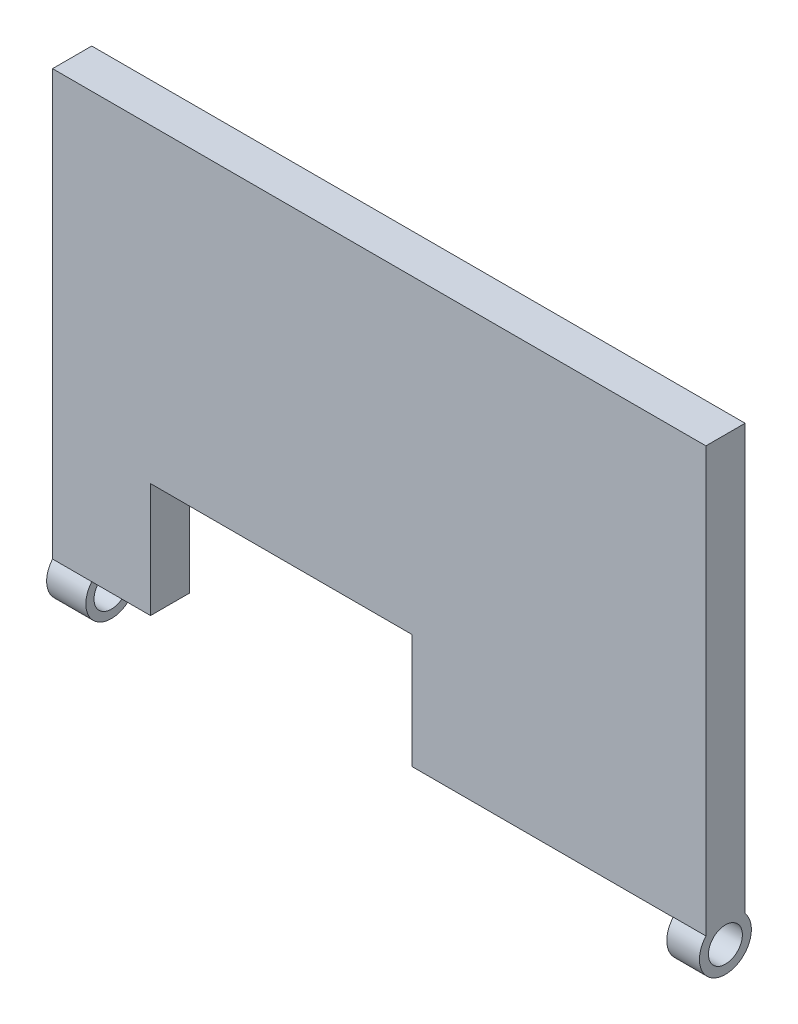
SolidWorks part; units mm, degrees
ref_plane "前视基准面" through (0, 0, 0) normal (0, 0, 1) x (1, 0, 0)
ref_plane "上视基准面" through (0, 0, 0) normal (0, 1, 0) x (1, 0, 0)
ref_plane "右视基准面" through (0, 0, 0) normal (1, 0, 0) x (0, 0, -1)
other "Configuration Table"
sketch "草图1" plane through (0, 0, 0) normal (0, 0, 1) x (1, 0, 0)
  line L0 (0, 0) -> (50, 0)
  line L1 (50, 0) -> (50, 65)
  line L2 (50, 65) -> (-50, 65)
  line L3 (-50, 65) -> (-50, 0)
  line L4 (-50, 0) -> (0, 0)
  dimension "D1" = 50
  dimension "D2" = 65
extrude "凸台-拉伸1" add sketch "草图1" along normal blind 6
sketch "草图2" plane through (-50, 0, 0) normal (-1, 0, 0) x (0, 0, 1)
  line L0 (3.0719, 64.8457) -> (3, 0) construction
  line L1 (6, 0) -> (0, 0) construction
  circle A1 centre (3, -2.5) radius 3.9051
  circle A2 centre (3, -2.5) radius 2.65
  dimension "D1" = 5.3
extrude "凸台-拉伸6" add sketch "草图2" against normal blind 6
sketch "草图3" plane through (50, 0, 0) normal (1, 0, 0) x (0, 0, -1)
  circle A1 centre (-3.0142, -2.5879) radius 3.9727
extrude "凸台-拉伸7" add sketch "草图3" against normal blind 5
sketch "草图4" plane through (45, 0, 0) normal (-1, 0, 0) x (0, 0, 1)
  circle A0 centre (3.0142, -2.5879) radius 2.6
  dimension "D1" = 5.2
extrude "切除-拉伸1" cut sketch "草图4" against normal blind 4.2 from offset 0.8 offset against normal yes
sketch "草图5" plane through (0, 0, 6) normal (0, 0, 1) x (1, 0, 0)
  line L0 (-35, 0) -> (-35, 17.5)
  line L1 (-44, 0) -> (45, 0) construction
  line L2 (-35, 17.5) -> (5, 17.5)
  line L3 (5, 17.5) -> (5, 0)
  line L4 (5, 0) -> (-35, 0)
  line L5 (-50, 65) -> (-50, 0) construction
  dimension "D1" = 17.5
  dimension "D2" = 15
  dimension "D3" = 40
extrude "切除-拉伸2" cut sketch "草图5" against normal blind 10
